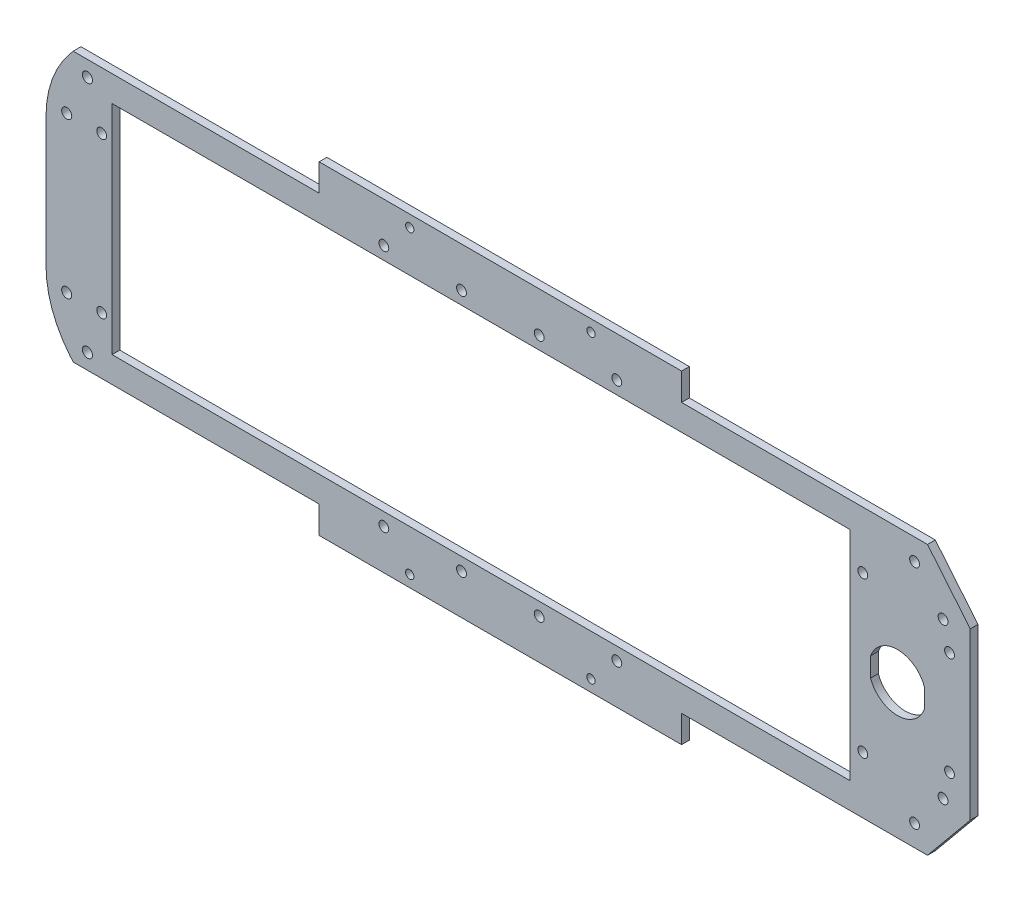
SolidWorks part; units mm, degrees
material "Acrylic (Medium-high impact)"
ref_plane "Front Plane" through (0, 0, 0) normal (0, 0, 1) x (1, 0, 0)
ref_plane "Top Plane" through (0, 0, 0) normal (0, 1, 0) x (1, 0, 0)
ref_plane "Right Plane" through (0, 0, 0) normal (1, 0, 0) x (0, 0, -1)
sketch "Sketch1" plane through (0, 0, 0) normal (0, 0, 1) x (1, 0, 0)
  line L1 (-70, 89.2972) -> (70, 89.2972)
  line L3 (-70, -35.7028) -> (70, -35.7028)
  line L10 (-70, 89.2972) -> (-70, 78.7972)
  line L11 (-70, 78.7972) -> (-165, 78.7972)
  line L12 (-165, -25.2028) -> (-70, -25.2028)
  line L13 (-70, -25.2028) -> (-70, -35.7028)
  line L14 (181.5, 26.7972) -> (-181.5, 26.7972) construction
  line L16 (165, 78.7972) -> (70, 78.7972)
  line L17 (70, 78.7972) -> (70, 89.2972)
  line L18 (70, -35.7028) -> (70, -25.2028)
  line L19 (70, -25.2028) -> (165, -25.2028)
  line L23 (0, 0) -> (0, 26.7972) construction
  line L24 (-150, 78.7972) -> (130, 78.7972) construction
  line L34 (-165, -25.2028) -> (-181.5, -5.2028)
  line L35 (-181.5, -5.2028) -> (-181.5, 58.7972)
  line L36 (-181.5, 58.7972) -> (-165, 78.7972)
  line L37 (165, 78.7972) -> (181.5, 58.7972)
  line L38 (181.5, 58.7972) -> (181.5, -5.2028)
  line L39 (181.5, -5.2028) -> (165, -25.2028)
  point P39 (36.064, 49.4641)
  dimension "D1" = 125
  dimension "D3" = 16.5
  dimension "D4" = 104
  dimension "D5" = 20
  dimension "D6" = 20
  dimension "D7" = 20
  dimension "D8" = 20
  dimension "D14" = 363
  dimension "D20" = 140
  dimension "D24" = 95
  dimension "D25" = 95
extrude "Boss-Extrude1" add sketch "Sketch1" along normal blind 3
sketch "Sketch2" plane through (0, 0, 3) normal (0, 0, 1) x (1, 0, 0)
  line L0 (-165, -25.2028) -> (-70, -25.2028) construction
  line L1 (-150, 68.7972) -> (135, 68.7972)
  line L2 (-150, 68.7972) -> (-150, -15.2028)
  line L3 (-150, -15.2028) -> (135, -15.2028)
  line L4 (135, 68.7972) -> (135, -15.2028)
  line L5 (-70, 78.7972) -> (-165, 78.7972) construction
  line L6 (70, -35.7028) -> (70, -25.2028) construction
  line L7 (-70, -25.2028) -> (-70, -35.7028) construction
  dimension "D1" = 10
  dimension "D2" = 10
  dimension "D3" = 65
  dimension "D4" = 80
extrude "Cut-Extrude1" cut sketch "Sketch2" against normal up to surface (3 mm away) up to face at (0, 26.7972, 0)
sketch "Sketch3" plane through (0, 0, 3) normal (0, 0, 1) x (1, 0, 0)
  line L0 (-167.5, -3.2028) -> (-167.5, 56.3751) construction
  line L1 (-181.5, 58.7972) -> (-181.5, -5.2028) construction
  line L2 (-167.5, 26.7972) -> (-181.5, 26.7972) construction
  line L3 (-70, -31.2028) -> (70, -31.2028) construction
  line L4 (-70, -25.2028) -> (-70, -35.7028) construction
  line L5 (70, -35.7028) -> (70, -25.2028) construction
  line L6 (-70, 84.7972) -> (70, 84.7972) construction
  line L7 (-70, 89.2972) -> (-70, 78.7972) construction
  line L8 (70, 78.7972) -> (70, 89.2972) construction
  line L9 (70, 89.2972) -> (-70, 89.2972) construction
  line L10 (-70, -35.7028) -> (70, -35.7028) construction
  line L11 (0, 89.2972) -> (0, -35.7028) construction
  line L12 (-35, -29.6028) -> (0, -29.6028) construction
  line L13 (35, -29.6028) -> (0, -29.6028) construction
  line L14 (-35, 83.1972) -> (0, 83.1972) construction
  line L15 (35, 83.1972) -> (0, 83.1972) construction
  line L16 (-70, 78.7972) -> (-165, 78.7972) construction
  line L17 (-165, -25.2028) -> (-70, -25.2028) construction
  line L18 (-159.5, 72.7972) -> (-159.5, -19.2028) construction
  circle A0 centre (-167.5, -3.2028) radius 1.95
  circle A3 centre (-167.5, 56.7972) radius 1.95
  circle A4 centre (-35, -31.2028) radius 1.6
  circle A5 centre (35, -31.2028) radius 1.6
  circle A6 centre (-35, 84.7972) radius 1.6
  circle A7 centre (35, 84.7972) radius 1.6
  circle A12 centre (-159.5, 72.7972) radius 1.95
  circle A13 centre (-159.5, -19.2028) radius 1.95
  circle A14 centre (-167.5, 26.7972) radius 1.95 [skipped]
  point P52 (-159.5, 26.7972)
  dimension "D1" = 3.9
  dimension "D8" = 3.2
  dimension "D11" = 3.9
  dimension "D3" = 30
  dimension "D4" = 14
  dimension "D5" = 6
  dimension "D6" = 6
  dimension "D7" = 35
  dimension "D12" = 92
  dimension "D13" = 5.5
  dimension "D2" = 3
extrude "Cut-Extrude2" cut sketch "Sketch3" against normal up to surface (3 mm away) up to face at (-7.5, 26.7972, 0)
sketch "Sketch4" plane through (0, 0, 3) normal (0, 0, 1) x (1, 0, 0)
  line L0 (163.8, 30.5312) -> (163.8, 23.0633)
  line L1 (143, 30.5312) -> (143, 23.0633)
  line L3 (135, 26.7972) -> (153.4, 26.7972) construction
  line L4 (135, -15.2028) -> (135, 68.7972) construction
  line L5 (153.4, 26.7972) -> (181.5, 26.7972) construction
  line L6 (181.5, -5.2028) -> (181.5, 58.7972) construction
  arc A0 (163.8, 30.5312) -> (143, 30.5312) centre (153.4, 26.7972) ccw
  arc A1 (143, 23.0633) -> (163.8, 23.0633) centre (153.4, 26.7972) ccw
  dimension "D1" = 22.1
  dimension "D2" = 20.8
  dimension "D3" = 8
extrude "Cut-Extrude3" cut sketch "Sketch4" against normal up to surface (3 mm away) up to face at (-36.6, 84.7972, 0)
sketch "Sketch5" plane through (0, 0, 3) normal (0, 0, 1) x (1, 0, 0)
  line L0 (181.5, 26.7972) -> (135, 26.7972) construction
  line L1 (181.5, -5.2028) -> (181.5, 58.7972) construction
  line L2 (135, -15.2028) -> (135, 68.7972) construction
  line L3 (173.5, 6.7972) -> (173.5, 46.7972) construction
  line L4 (140, 56.7972) -> (140, -3.2028) construction
  line L5 (160, 70.5472) -> (160, -16.9528) construction
  circle A0 centre (173.5, 6.7972) radius 1.9
  circle A1 centre (173.5, 46.7972) radius 1.9
  circle A2 centre (140, 56.7972) radius 1.9
  circle A3 centre (140, -3.2028) radius 1.9
  circle A4 centre (160, 70.5472) radius 1.9
  circle A6 centre (160, -16.9528) radius 1.9
  point P20 (160, 26.7972)
  dimension "D1" = 3.8
  dimension "D9" = 3.8
  dimension "D12" = 3.8
  dimension "D3" = 8
  dimension "D4" = 20
  dimension "D5" = 20
  dimension "D6" = 30
  dimension "D7" = 30
  dimension "D8" = 5
  dimension "D10" = 87.5
  dimension "D11" = 5
  dimension "D2" = 2
extrude "Cut-Extrude4" cut sketch "Sketch5" against normal up to surface (3 mm away) up to face at (153.4, 26.7972, 0)
sketch "Sketch7" plane through (0, 0, 3) normal (0, 0, 1) x (1, 0, 0)
  line L0 (-181.5, 58.7972) -> (-181.5, -5.2028) construction
  line L2 (-175.5, 89.6705) -> (-212.0856, 89.6705)
  line L3 (-175.5, 89.6705) -> (-175.5, -21.5244)
  line L4 (-175.5, -21.5244) -> (-212.0856, -21.5244)
  line L5 (-212.0856, 89.6705) -> (-212.0856, -21.5244)
  point P3 (-173.2816, 26.7972)
  dimension "D1" = 6
extrude "Cut-Extrude5" cut sketch "Sketch7" against normal blind 10
fillet "Fillet1" radius 40 2 edges at (-175.5, -12.4755, 1.5) (-175.5, 66.07, 1.5)
sketch "Sketch6" plane through (0, 0, 3) normal (0, 0, 1) x (1, 0, 0)
  line L0 (-135.5333, 73.7972) -> (160.4477, 73.7972) construction
  line L1 (-161.7261, -20.2028) -> (140.015, -20.2028) construction
  line L2 (-154, 56.7972) -> (-154, -3.2028) construction
  line L3 (-150, 68.7972) -> (-150, -15.2028) construction
  line L4 (-70, 89.2972) -> (-70, 78.7972) construction
  line L5 (135, 68.7972) -> (-150, 68.7972) construction
  line L6 (-150, -15.2028) -> (135, -15.2028) construction
  circle A0 centre (171, 56.7972) radius 1.9
  circle A1 centre (171, -3.2028) radius 1.9
  circle A2 centre (-154, 56.7972) radius 1.9
  circle A3 centre (-154, -3.2028) radius 1.9
  circle A4 centre (-45, 73.7972) radius 1.9
  circle A5 centre (-45, -20.2028) radius 1.9
  circle A6 centre (-15, -20.2028) radius 1.9
  circle A7 centre (-15, 73.7972) radius 1.9
  circle A8 centre (15, -20.2028) radius 1.9
  circle A9 centre (15, 73.7972) radius 1.9
  circle A10 centre (45, -20.2028) radius 1.9
  circle A11 centre (45, 73.7972) radius 1.9
  circle A14 centre (75, 73.7972) radius 1.9 [skipped]
  circle A15 centre (75, -20.2028) radius 1.9 [skipped]
  point P14 (-150, 26.7972)
  point P15 (-154, 26.7972)
  dimension "D2" = 3.8
  dimension "D1" = 60
  dimension "D3" = 25
  dimension "D4" = 5
  dimension "D5" = 5
  dimension "D7" = 325
  dimension "D8" = 4
  dimension "D6" = 5
extrude "Expansion mounting holes" cut sketch "Sketch6" against normal blind 10
